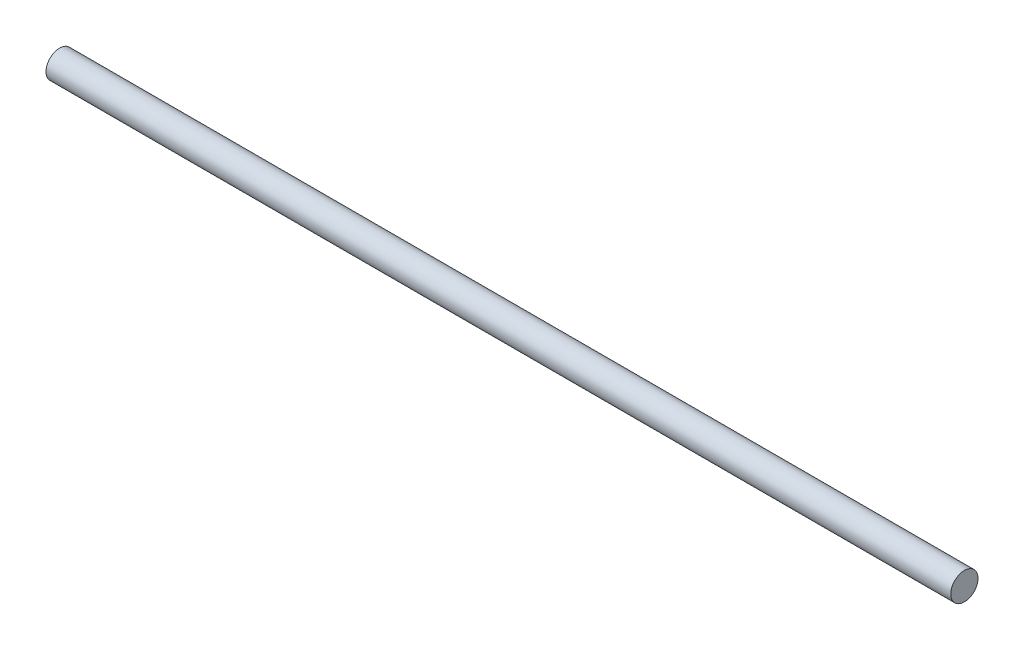
SolidWorks part; units mm, degrees
ref_plane "Front Plane" through (0, 0, 0) normal (0, 0, 1) x (1, 0, 0)
ref_plane "Top Plane" through (0, 0, 0) normal (0, 1, 0) x (1, 0, 0)
ref_plane "Right Plane" through (0, 0, 0) normal (1, 0, 0) x (0, 0, -1)
sketch "Sketch1" plane through (0, 0, 0) normal (1, 0, 0) x (0, 0, -1)
  circle A0 centre (0, 0) radius 7.5
extrude "Boss-Extrude1" add sketch "Sketch1" along normal blind 497.5
